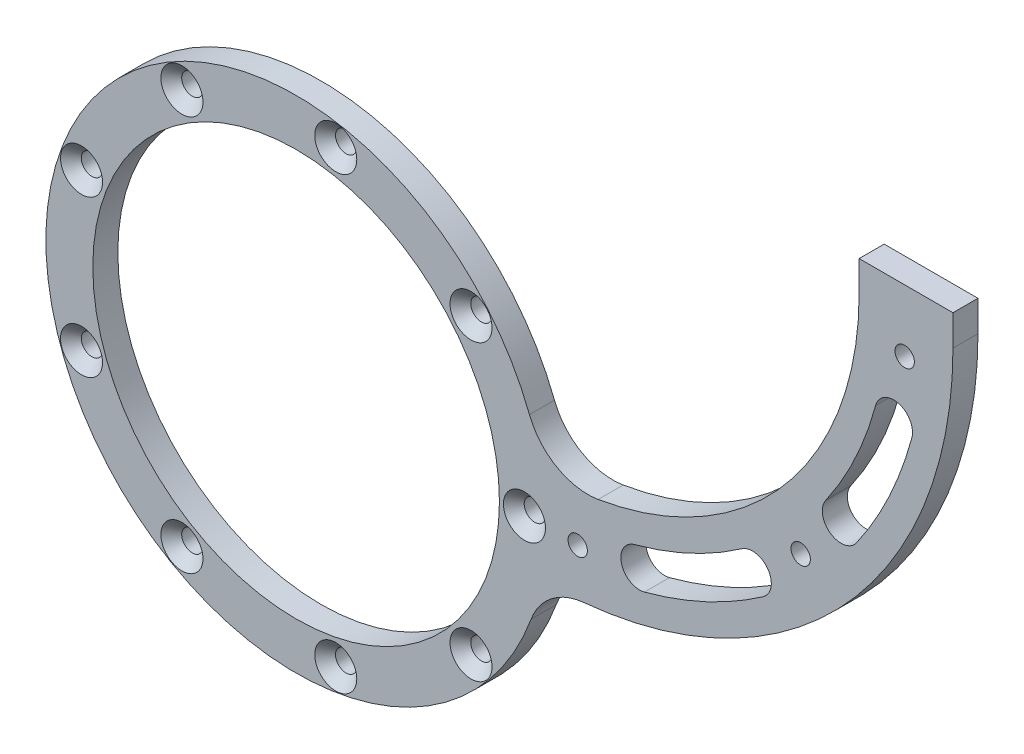
SolidWorks part; units mm, degrees
material "Thornel Mat VMA"
ref_plane "前视基准面" through (0, 0, 0) normal (0, 0, 1) x (1, 0, 0)
ref_plane "上视基准面" through (0, 0, 0) normal (0, 1, 0) x (1, 0, 0)
ref_plane "右视基准面" through (0, 0, 0) normal (1, 0, 0) x (0, 0, -1)
other "Configuration Table"
sketch "草图1" plane through (0, 0, 0) normal (0, 0, 1) x (1, 0, 0)
  circle A0 centre (0, 0) radius 40
  circle A10 centre (0, 0) radius 32.5
  dimension "D1" = 80
  dimension "D6" = 65
extrude "凸台-拉伸1" add sketch "草图1" along normal blind 4
sketch "草图2" plane through (0, 0, 4) normal (0, 0, 1) x (1, 0, 0)
  line L0 (0, 0) -> (40, 0) construction
  line L1 (0, 0) -> (36.5, 0) construction
  circle A0 centre (0, 0) radius 40 construction
  point P6 (36.5, 0)
  point P7 (27.9606, -23.4617)
  point P10 (6.3382, -35.9455)
  point P11 (-18.25, -31.6099)
  point P12 (-34.2988, -12.4837)
  point P13 (-34.2988, 12.4837)
  point P14 (-18.25, 31.6099)
  point P15 (6.3382, 35.9455)
  point P16 (27.9606, 23.4617)
  dimension "D3" = 36.5
  dimension "D2" = 9
hole_wizard "M3 六角凹锥坑螺钉的锥形沉头孔1" positions "草图2" profile "草图3" countersink size "M3" standard "ISO" end condition through all
sketch "草图3" plane through (27.9606, 23.4617, 4) normal (1, 0, 0) x (0, -1, 0)
  line L0 (0, 0) -> (0, 4)
  line L1 (0, 4) -> (1.7, 4)
  line L2 (1.7, 4) -> (1.7, 1.66)
  line L3 (1.7, 1.66) -> (3.36, 0)
  line L5 (3.36, 0) -> (0, 0)
  line L6 (-1.7, 1.66) -> (-3.36, 0) construction
  line L11 (0, -6.35) -> (0, 107.95) construction
  dimension "通孔孔直径" = 3.4
  dimension "通孔孔深度" = 4
  dimension "近端锥形沉头孔直径" = 6.72
  dimension "近端锥形沉头孔角度" = 90
sketch "草图4" plane through (0, 0, 4) normal (0, 0, 1) x (1, 0, 0)
  line L0 (0, 0) -> (40, 0) construction
  line L1 (40, 0) -> (40, 57.5) construction
  line L2 (40, 57.5) -> (97.5, 57.5) construction
  line L3 (45.0115, 0.2188) -> (40, 57.5) construction
  line L4 (40, 57.5) -> (97.2812, 52.4885) construction
  line L5 (80.6586, 16.8414) -> (40, 57.5) construction
  line L6 (92.1127, 33.1994) -> (40, 57.5) construction
  line L7 (90, 57.5) -> (105, 57.5)
  line L14 (40, 57.5) -> (64.3006, 5.3873) construction
  circle A0 centre (0, 0) radius 40 construction
  arc A5 (40, 0) -> (97.5, 57.5) centre (40, 57.5) ccw construction
  arc A18 (90, 57.5) -> (39.2896, 7.505) centre (40, 57.5) cw
  circle A26 centre (45.0115, 0.2188) radius 1.55
  circle A27 centre (80.6586, 16.8414) radius 1.55
  circle A28 centre (97.2812, 52.4885) radius 1.55
  arc A29 (54.9043, 1.9652) -> (72.9618, 10.3856) centre (40, 57.5) ccw construction
  arc A30 (55.6819, -0.9322) -> (74.6816, 7.9274) centre (40, 57.5) ccw
  arc A31 (54.1267, 4.8627) -> (71.2421, 12.8437) centre (40, 57.5) ccw
  arc A32 (54.1267, 4.8627) -> (55.6819, -0.9322) centre (54.9043, 1.9652) ccw
  arc A33 (74.6816, 7.9274) -> (71.2421, 12.8437) centre (72.9618, 10.3856) ccw
  arc A34 (87.1144, 24.5382) -> (95.5348, 42.5957) centre (40, 57.5) ccw construction
  arc A35 (89.5726, 22.8184) -> (98.4322, 41.8181) centre (40, 57.5) ccw
  arc A36 (84.6563, 26.2579) -> (92.6373, 43.3733) centre (40, 57.5) ccw
  arc A37 (84.6563, 26.2579) -> (89.5726, 22.8184) centre (87.1144, 24.5382) ccw
  arc A38 (98.4322, 41.8181) -> (92.6373, 43.3733) centre (95.5348, 42.5957) ccw
  arc A41 (105, 57.5) -> (39.2913, -7.4961) centre (40, 57.5) cw
  arc A42 (39.2896, 7.505) -> (39.2913, -7.4961) centre (0, 0) cw
  point P15 (64.3006, 5.3873)
  point P20 (92.1127, 33.1994)
  dimension "D2" = 50
  dimension "D8" = 3.1
  dimension "D9" = 3.1
  dimension "D10" = 3
  dimension "D15" = 25
  dimension "D16" = 25
  dimension "D6" = 3.1
  dimension "D11" = 3
  dimension "D3" = 65
  dimension "D4" = 57.5
  dimension "D5" = 57.5
  dimension "D7" = 5
  dimension "D12" = 10
  dimension "D13" = 10
  dimension "D14" = 5
  dimension "D17" = 45
extrude "凸台-拉伸2" add sketch "草图4" against normal up to surface (4 mm away) up to face at (38.2, 0, 0)
fillet "圆角1" radius 10 2 edges at (39.2913, -7.4961, 2) (39.2896, 7.505, 2)
sketch "草图5" plane through (0, 0, 4) normal (0, 0, 1) x (1, 0, 0)
  line L1 (90, 62.4) -> (105, 62.4)
  line L2 (90, 62.4) -> (90, 57.5)
  line L3 (90, 57.5) -> (105, 57.5)
  line L4 (105, 62.4) -> (105, 57.5)
  dimension "D1" = 4.9
extrude "凸台-拉伸3" add sketch "草图5" against normal up to surface (4 mm away) up to face at (38.2, 0, 0)
